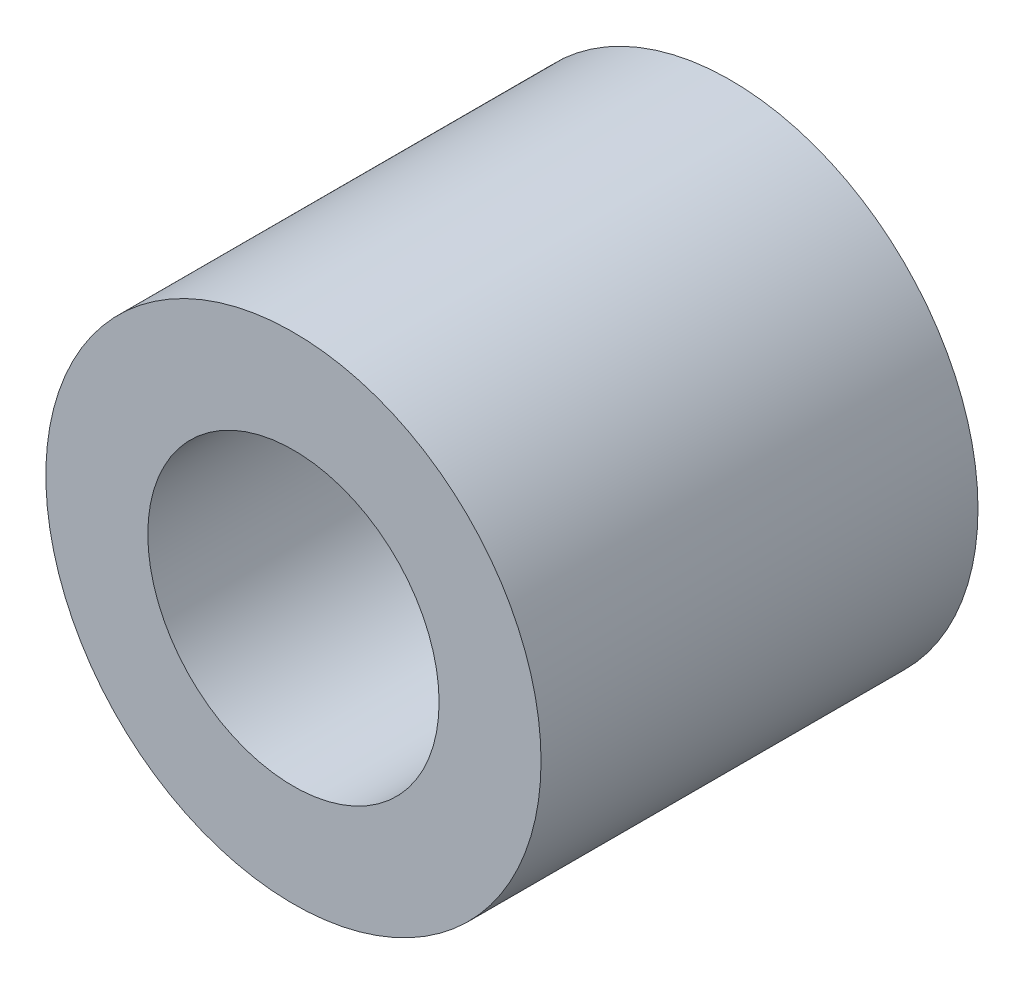
SolidWorks part; units mm, degrees
ref_plane "Front Plane" through (0, 0, 0) normal (0, 0, 1) x (1, 0, 0)
ref_plane "Top Plane" through (0, 0, 0) normal (0, 1, 0) x (1, 0, 0)
ref_plane "Right Plane" through (0, 0, 0) normal (1, 0, 0) x (0, 0, -1)
sketch "Sketch1" plane through (0, 0, 0) normal (0, 0, 1) x (1, 0, 0)
  circle A0 centre (0, 0) radius 5
  circle A1 centre (0, 0) radius 8.5
  dimension "D1" = 10
  dimension "D2" = 17
extrude "Boss-Extrude1" add sketch "Sketch1" along normal mid plane 15
